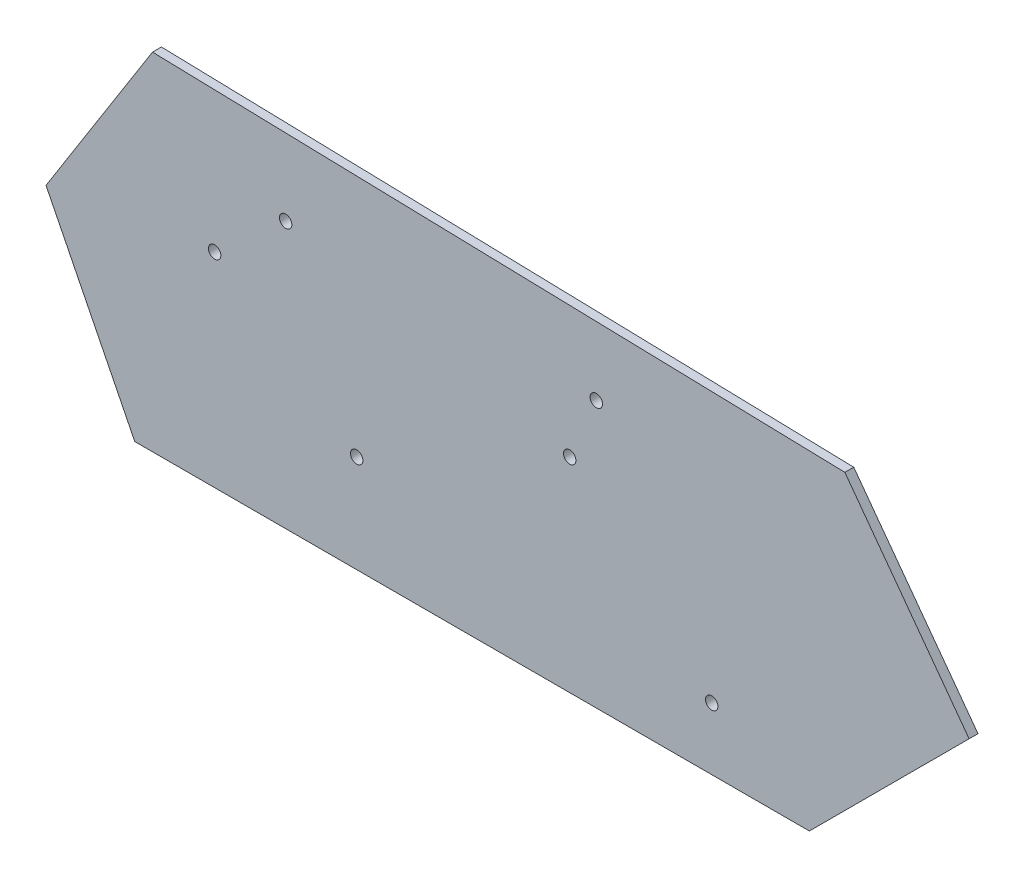
SolidWorks part; units mm, degrees
ref_plane "前视基准面" through (0, 0, 0) normal (0, 0, 1) x (1, 0, 0)
ref_plane "上视基准面" through (0, 0, 0) normal (0, 1, 0) x (1, 0, 0)
ref_plane "右视基准面" through (0, 0, 0) normal (1, 0, 0) x (0, 0, -1)
other "Configuration Table"
sketch "草图1" plane through (0, 0, 0) normal (0, 0, 1) x (1, 0, 0)
  line L0 (-175, 45) -> (-125, -55)
  line L1 (-125, -55) -> (255, -55)
  line L2 (255, -55) -> (345, 35)
  line L3 (345, 35) -> (275, 130)
  line L4 (275, 130) -> (-115, 140)
  line L5 (-115, 140) -> (-175, 45)
  circle A0 centre (0, 0) radius 3.5
  circle A1 centre (-80, 60) radius 3.5
  circle A2 centre (120, 60) radius 3.5
  circle A3 centre (200, -20) radius 3.5
  circle A4 centre (-40, 95) radius 3.5
  circle A5 centre (135, 95) radius 3.5
extrude "凸台-拉伸1" add sketch "草图1" along normal blind 5
